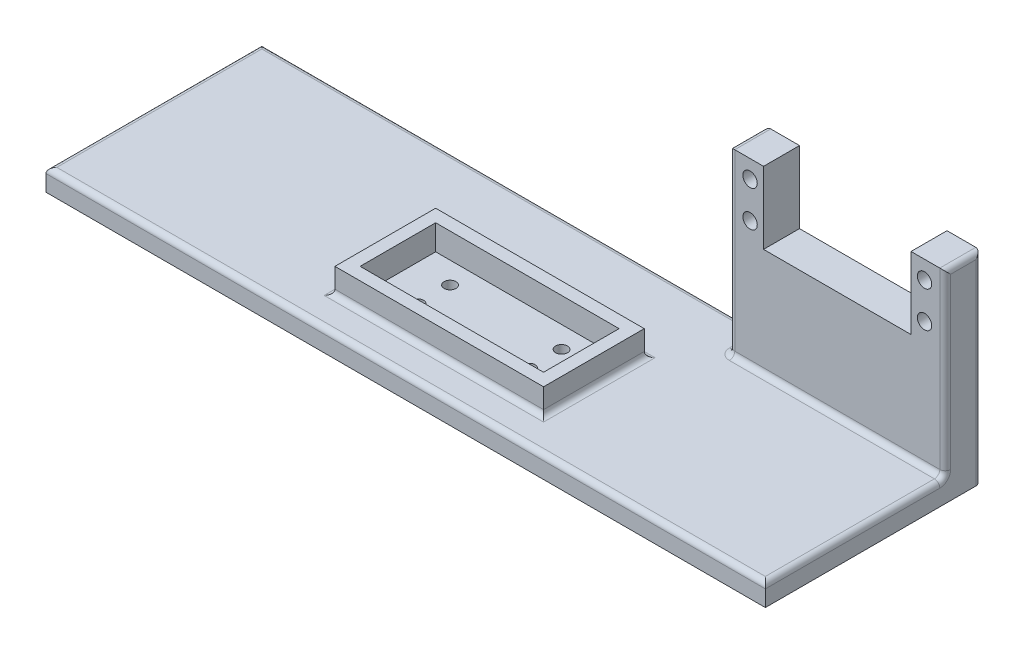
SolidWorks part; units mm, degrees
ref_plane "Front Plane" through (0, 0, 0) normal (0, 0, 1) x (1, 0, 0)
ref_plane "Top Plane" through (0, 0, 0) normal (0, 1, 0) x (1, 0, 0)
ref_plane "Right Plane" through (0, 0, 0) normal (1, 0, 0) x (0, 0, -1)
sketch "Sketch8" plane through (0, 0, 0) normal (0, 1, 0) x (1, 0, 0)
  line L1 (-100, -30) -> (100, -30)
  line L2 (-100, -30) -> (-100, 30)
  line L3 (-100, 30) -> (100, 30)
  line L4 (100, -30) -> (100, 30)
  line L5 (-100, -30) -> (100, 30) construction
  line L6 (-100, 30) -> (100, -30) construction
  point P0 (0, 0)
  dimension "D1" = 60
  dimension "D2" = 200
extrude "Boss-Extrude6" add sketch "Sketch8" along normal blind 6
sketch "Sketch9" plane through (0, 6, 0) normal (0, 1, 0) x (1, 0, 0)
  line L0 (100, -30) -> (100, 30) construction
  line L1 (100, 30) -> (40, 30)
  line L2 (100, 30) -> (100, 20)
  line L3 (100, 20) -> (40, 20)
  line L4 (40, 30) -> (40, 20)
  dimension "D1" = 10
  dimension "D2" = 60
extrude "Boss-Extrude7" add sketch "Sketch9" along normal blind 50
sketch "Sketch10" plane through (0, 0, -20) normal (0, 0, 1) x (1, 0, 0)
  line L6 (40, 56) -> (100, 56) construction
  line L7 (90.5, 56) -> (49.5, 56)
  line L8 (90.5, 56) -> (90.5, 36)
  line L9 (90.5, 36) -> (49.5, 36)
  line L10 (49.5, 56) -> (49.5, 36)
  line L11 (49.5, 56) -> (40, 56) construction
  line L12 (90.5, 56) -> (100, 56) construction
  line L13 (45.75, 41) -> (45.75, 51) construction
  line L14 (70, 56) -> (70, 36) construction
  circle A4 centre (45.75, 51) radius 2
  circle A5 centre (45.75, 41) radius 2
  circle A6 centre (94.25, 51) radius 2
  circle A7 centre (94.25, 41) radius 2
  point P26 (45.75, 46)
  point P27 (49.5, 46)
  point P30 (70, 56)
  line M11 (100, 56) -> (40, 56)
  dimension "D9" = 4
  dimension "D7" = 41
  dimension "D8" = 20
  dimension "D10" = 10
  dimension "D11" = 24.25
ref_plane "TowerOffsetPlane" through (0, 0, 7.7) normal (0, 0, 1) x (1, 0, 0)
sketch "Sketch11" plane through (0, 0, 7.7) normal (0, 0, 1) x (1, 0, 0)
  line L0 (-100, 6) -> (100, 6) construction
  line L2 (-4.8939, 102.0247) -> (-25, 6)
  line L3 (4.8939, 102.0247) -> (25, 6)
  line L4 (-25, 6) -> (25, 6)
  line L5 (100, 6) -> (100, 0) construction
  circle A0 centre (0, 101) radius 3.175
  arc A1 (4.8939, 102.0247) -> (-4.8939, 102.0247) centre (0, 101) ccw
  point P9 (0, 6)
  dimension "D2" = 6.35
  dimension "D4" = 10
  dimension "D1" = 95
  dimension "D5" = 50
  dimension "D3" = 100
extrude "Boss-Extrude8" [suppressed] add sketch "Sketch11" along normal mid plane 10 contours A0 | L3 L4 L2 A1
extrude "Cut-Extrude8" cut sketch "Sketch10" against normal up to surface (10 mm away) contours A4 | A5 | L10 L9 L8 M11 | A6 | A7 up to face at (13.3333, 20.6667, -30)
sketch "Sketch15" plane through (0, 6, 0) normal (0, 1, 0) x (1, 0, 0)
  line L0 (100, -30) -> (100, 20) construction
  line L1 (-29, 7.3312) -> (29, 7.3312)
  line L2 (-29, 7.3312) -> (-29, -20.6688)
  line L3 (-29, -20.6688) -> (29, -20.6688)
  line L4 (29, 7.3312) -> (29, -20.6688)
  line L5 (40, 30) -> (-100, 30) construction
  point P4 (0, 7.3312)
  point P7 (29, -6.6688)
  dimension "D1" = 100
  dimension "D2" = 36.6688
  dimension "D3" = 28
  dimension "D4" = 58
extrude "Boss-Extrude9" add sketch "Sketch15" along normal blind 7
sketch "Sketch12" plane through (0, 13, 0) normal (0, 1, 0) x (1, 0, 0)
  line L1 (-25.5, 3.8312) -> (25.5, 3.8312)
  line L2 (-25.5, 3.8312) -> (-25.5, -17.1688)
  line L3 (-25.5, -17.1688) -> (25.5, -17.1688)
  line L4 (25.5, 3.8312) -> (25.5, -17.1688)
  line L10 (-29, 7.3312) -> (-29, -20.6688) construction
  line L11 (29, 7.3312) -> (-29, 7.3312) construction
  line L12 (29, -20.6688) -> (29, 7.3312) construction
  line L13 (-29, -20.6688) -> (29, -20.6688) construction
  dimension "D1" = 3.5
  dimension "D2" = 3.5
  dimension "D3" = 3.5
  dimension "D4" = 3.5
extrude "Cut-Extrude9" cut sketch "Sketch12" against normal blind 7
sketch "Sketch13" plane through (0, 0, 0) normal (0, -1, 0) x (-1, 0, 0)
  line L1 (-25.5, 3.8312) -> (25.5, 3.8312) construction
  line L2 (-25.5, 3.8312) -> (-25.5, -17.1688) construction
  line L3 (-25.5, -17.1688) -> (25.5, -17.1688) construction
  line L4 (25.5, 3.8312) -> (25.5, -17.1688) construction
  line L11 (-25.5, 3.8312) -> (25.5, 3.8312) construction
  line L12 (25.5, -17.1688) -> (-25.5, -17.1688) construction
  line L13 (25.5, 3.8312) -> (25.5, -17.1688) construction
  line L14 (-25.5, -17.1688) -> (-25.5, 3.8312) construction
  circle A0 centre (-15.5, -2.1688) radius 3
  circle A1 centre (-15.5, -11.1688) radius 3
  circle A4 centre (15.5, -2.1688) radius 3
  circle A5 centre (15.5, -11.1688) radius 3
  dimension "D4" = 10
  dimension "D5" = 6
  dimension "D2" = 6
extrude "Cut-Extrude10" cut sketch "Sketch13" against normal blind 2
sketch "Sketch17" plane through (0, 2, 0) normal (0, -1, 0) x (1, 0, 0)
  circle A0 centre (-15.5, 11.1688) radius 1.65
  circle A1 centre (-15.5, 2.1688) radius 1.65
  circle A4 centre (15.5, 11.1688) radius 1.65
  circle A5 centre (15.5, 2.1688) radius 1.65
  point P6 (0, 0)
  dimension "D1" = 3.3
extrude "Cut-Extrude11" cut sketch "Sketch17" against normal up to surface (4 mm away) up to face at (0, 6, 6.6688)
fillet "Fillet1" radius 1.5 4 edges at (0, 6, -7.3312) (29, 6, 6.6688) (0, 6, 20.6688) (-29, 6, 6.6688)
fillet "Fillet2" radius 1.5 12 edges at (100, 31, -20) (40, 31, -30) (100, 6, 5) (0, 6, 30) (-100, 6, 0) (-30, 6, -30) (40, 6, -25) (70, 6, -20) (100, 28, -30) (100, 56, -25) (40, 56, -25) (40, 31, -20)
equation "\"base_length\"=200"
equation "\"hole_diameter\"= 3in / 16"
equation "\"bearing_slot_diameter\"= 1in / 4"
equation "\"base_width\"=60"
equation "\"D1@Sketch8\"= \"base_width\""
equation "\"D2@Sketch8\"=\"base_length\""
equation "\"base_thickness\"=6"
equation "\"D1@Boss-Extrude6\"=\"base_thickness\""
equation "\"tower_height\"= 95mm"
equation "\"D1@Sketch11\"=\"tower_height\""
equation "\"D2@Sketch11\"=\"bearing_slot_diameter\""
equation "\"tower_offset_z\"= 32.2mm + 5in / 32 + 1mm / 2"
equation "\"tower_offset_x\"= 100mm"
equation "\"D3@Sketch11\"=\"tower_offset_x\""
equation "\"D1@Sketch15\"=\"tower_offset_x\""
equation "\"D2@Sketch15\"=\"tower_offset_z\""
equation "\"tower_base_height\"=7"
equation "\"D1@Boss-Extrude9\"=\"tower_base_height\""
equation "\"tower_base_depth\"=9"
equation "\"D1@Cut-Extrude9\"=\"tower_base_height\""
equation "\"D2@Sketch12\"=\"D1@Sketch12\""
equation "\"D3@Sketch12\"=\"D1@Sketch12\""
equation "\"D4@Sketch12\"=\"D1@Sketch12\""
equation "\"D2@Sketch13\"=\"D1@Sketch13\""
equation "\"D3@Sketch13\"=10mm"
equation "\"D4@Sketch13\"=\"D3@Sketch13\""
